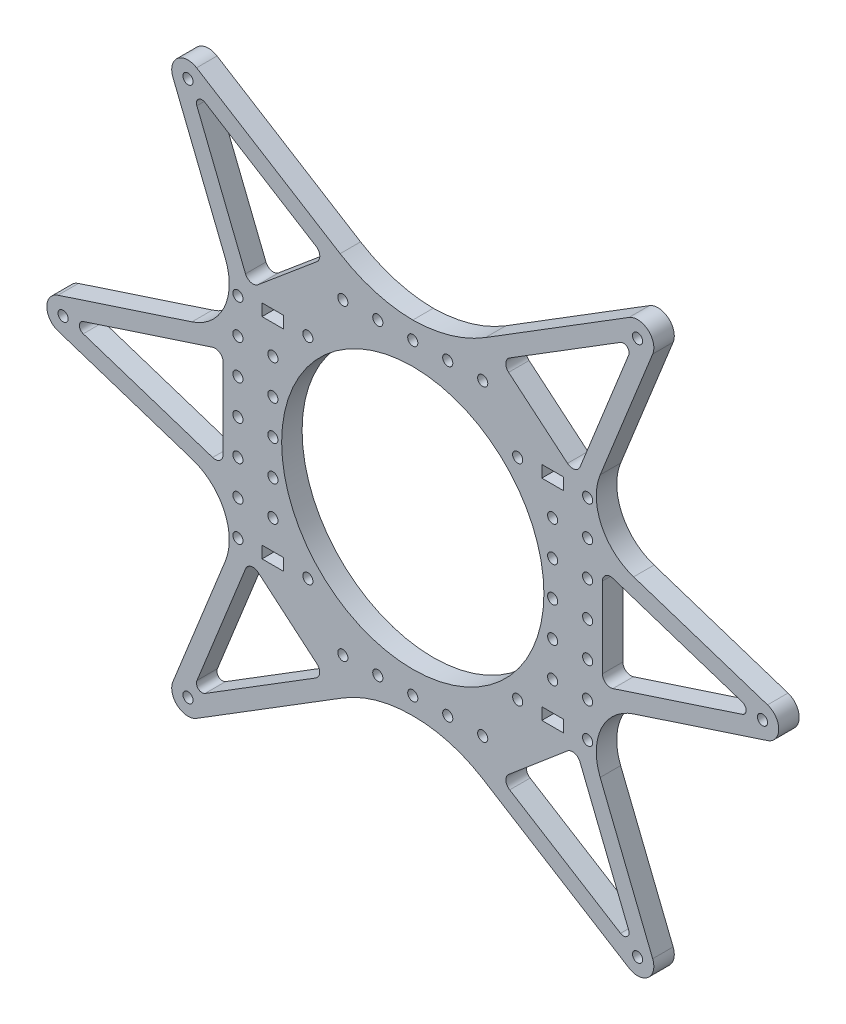
SolidWorks part; units mm, degrees
material "Acrylic (Medium-high impact)"
ref_plane "Front Plane" through (0, 0, 0) normal (0, 0, 1) x (1, 0, 0)
ref_plane "Top Plane" through (0, 0, 0) normal (0, 1, 0) x (1, 0, 0)
ref_plane "Right Plane" through (0, 0, 0) normal (1, 0, 0) x (0, 0, -1)
sketch "Sketch1" plane through (0, 0, 0) normal (0, 0, 1) x (1, 0, 0)
  line L0 (-447622.4345, 422.8828) -> (448935.6268, 422.8828) construction
  line L1 (587.9953, 497.7534) -> (603.0011, 460.347)
  line L2 (696.5962, 452.8828) -> (696.5962, 392.8828) construction
  line L3 (653.3971, 419.0702) -> (-31485.9834, -37883.1519) construction
  line L4 (699.6962, 394.5828) -> (693.4962, 391.1828) construction
  line L5 (699.6962, 391.1828) -> (693.4962, 394.5828) construction
  line L6 (594.8522, 494.09) -> (608.7611, 459.4182)
  line L7 (594.7755, 503.4426) -> (635.8224, 477.9343)
  line L8 (597.1925, 496.0537) -> (628.9222, 476.3355)
  line L9 (594.8522, 494.09) -> (597.1925, 496.0537) construction
  line L10 (699.6962, 391.1828) -> (693.4962, 391.1828)
  line L11 (693.4962, 394.5828) -> (693.4962, 391.1828)
  line L12 (699.6962, 394.5828) -> (693.4962, 394.5828)
  line L13 (594.7755, 503.4426) -> (587.9953, 497.7534) construction
  line L14 (629.1852, 472.64) -> (612.3548, 458.5175)
  line L15 (608.7611, 459.4182) -> (628.9222, 476.3355) construction
  line L16 (699.6962, 394.5828) -> (699.6962, 391.1828)
  line L17 (-343.4038, 422.8828) -> (49656.5962, 422.8828) construction
  line L18 (648.8948, 432.061) -> (-31490.4849, 38734.2822) construction
  line L19 (-347.3366, 471.8828) -> (49652.6634, 471.8828) construction
  line L20 (-347.2527, 373.8828) -> (49652.7473, 373.8828) construction
  line L21 (562.3601, 421.3552) -> (599.3601, 409.2322)
  line L22 (602.3601, 434.3594) -> (602.3601, 411.4062)
  line L23 (555.1462, 427.3082) -> (555.1462, 418.4573) construction
  line L24 (562.3601, 424.4103) -> (599.3601, 436.5334)
  line L25 (599.3601, 409.2322) -> (599.3601, 436.5334) construction
  line L26 (555.1462, 427.3082) -> (593.4467, 439.8574)
  line L27 (562.3601, 421.3552) -> (562.3601, 424.4103) construction
  line L28 (555.1462, 418.4573) -> (593.4517, 405.9065)
  line L29 (594.8972, 351.7804) -> (608.794, 386.3972)
  line L30 (594.7731, 342.323) -> (636.5319, 368.249)
  line L31 (612.3844, 387.288) -> (629.1561, 373.0862)
  line L32 (613.4962, 451.1828) -> (619.6962, 454.5828) construction
  line L33 (613.4962, 454.5828) -> (619.6962, 451.1828) construction
  line L34 (597.1926, 349.7104) -> (594.8972, 351.7804) construction
  line L35 (587.9969, 348.0128) -> (594.7731, 342.323) construction
  line L36 (628.8837, 369.3858) -> (608.794, 386.3972) construction
  line L37 (597.1926, 349.7104) -> (628.8837, 369.3858)
  line L38 (587.9969, 348.0128) -> (603.0082, 385.4059)
  line L39 (613.4962, 391.1828) -> (619.6962, 394.5828) construction
  line L40 (699.6962, 454.5828) -> (693.4962, 451.1828) construction
  line L41 (613.4962, 394.5828) -> (619.6962, 391.1828) construction
  line L42 (616.5962, 452.8828) -> (616.5962, 392.8828) construction
  line L43 (699.6962, 451.1828) -> (693.4962, 454.5828) construction
  line L44 (684.3087, 369.3858) -> (704.3983, 386.3972) construction
  line L45 (725.1955, 348.0128) -> (718.4193, 342.323) construction
  line L46 (715.9998, 349.7104) -> (718.2951, 351.7804) construction
  line L47 (750.8323, 421.3552) -> (750.8323, 424.4103) construction
  line L48 (713.8323, 409.2322) -> (713.8323, 436.5334) construction
  line L49 (758.0462, 427.3082) -> (758.0462, 418.4573) construction
  line L50 (704.4313, 459.4182) -> (684.2701, 476.3355) construction
  line L51 (718.4169, 503.4426) -> (725.1971, 497.7534) construction
  line L52 (718.3402, 494.09) -> (715.9998, 496.0537) construction
  line L53 (613.4962, 454.5828) -> (619.6962, 454.5828)
  line L54 (619.6962, 451.1828) -> (619.6962, 454.5828)
  line L55 (613.4962, 451.1828) -> (619.6962, 451.1828)
  line L56 (699.6962, 451.1828) -> (699.6962, 454.5828)
  line L57 (699.6962, 451.1828) -> (693.4962, 451.1828)
  line L58 (693.4962, 451.1828) -> (693.4962, 454.5828)
  line L59 (699.6962, 454.5828) -> (693.4962, 454.5828)
  line L60 (725.1955, 348.0128) -> (710.1842, 385.4059)
  line L61 (715.9998, 349.7104) -> (684.3087, 369.3858)
  line L62 (700.808, 387.288) -> (684.0362, 373.0862)
  line L63 (718.4193, 342.323) -> (676.6605, 368.249)
  line L64 (718.2951, 351.7804) -> (704.3983, 386.3972)
  line L65 (758.0462, 418.4573) -> (719.7407, 405.9065)
  line L66 (758.0462, 427.3082) -> (719.7457, 439.8574)
  line L67 (750.8323, 424.4103) -> (713.8323, 436.5334)
  line L68 (710.8323, 434.3594) -> (710.8323, 411.4062)
  line L69 (750.8323, 421.3552) -> (713.8323, 409.2322)
  line L70 (613.4962, 451.1828) -> (613.4962, 454.5828)
  line L71 (684.0071, 472.64) -> (700.8376, 458.5175)
  line L72 (613.4962, 394.5828) -> (613.4962, 391.1828)
  line L73 (613.4962, 394.5828) -> (619.6962, 394.5828)
  line L74 (619.6962, 394.5828) -> (619.6962, 391.1828)
  line L75 (715.9998, 496.0537) -> (684.2701, 476.3355)
  line L76 (718.4169, 503.4426) -> (677.3699, 477.9343)
  line L77 (718.3402, 494.09) -> (704.4313, 459.4182)
  line L78 (725.1971, 497.7534) -> (710.1912, 460.347)
  line L79 (613.4962, 391.1828) -> (619.6962, 391.1828)
  line L80 (706.5962, 432.8828) -> (696.5962, 432.8828) construction
  line L81 (706.5962, 422.8828) -> (706.5962, 432.8828) construction
  line L111 (656.5962, -513.6368) -> (656.5962, 49486.3632) construction
  arc A0 (597.1925, 496.0537) -> (594.8522, 494.09) centre (596.3441, 494.6884) ccw
  arc A1 (587.9953, 497.7534) -> (594.7755, 503.4426) centre (592.3174, 499.4872) cw
  circle A2 centre (592.3174, 499.4872) radius 1.45
  arc A4 (608.7611, 459.4182) -> (612.3548, 458.5175) centre (610.8843, 460.27) ccw
  arc A5 (629.1852, 472.64) -> (628.9222, 476.3355) centre (627.7147, 474.3924) ccw
  circle A6 centre (592.3174, 499.4872) radius 4.6569 construction
  circle A7 centre (706.5962, 432.8828) radius 1.45
  circle A8 centre (706.5962, 442.8828) radius 1.45
  circle A9 centre (706.5962, 452.8828) radius 1.45
  circle A10 centre (706.5962, 392.8828) radius 1.45
  arc A11 (555.1462, 418.4573) -> (555.1462, 427.3082) centre (556.5962, 422.8828) cw
  circle A12 centre (556.5962, 422.8828) radius 1.45
  circle A13 centre (646.5962, 378.8828) radius 1.45
  circle A14 centre (556.5962, 422.8828) radius 4.6569 construction
  arc A15 (562.3601, 424.4103) -> (562.3601, 421.3552) centre (562.8606, 422.8828) ccw
  circle A16 centre (656.5962, 422.8828) radius 37.5
  circle A18 centre (636.5962, 378.8828) radius 1.45
  arc A19 (602.3601, 434.3594) -> (599.3601, 436.5334) centre (600.0724, 434.3594) ccw
  circle A20 centre (706.5962, 402.8828) radius 1.45
  arc A21 (599.3601, 409.2322) -> (602.3601, 411.4062) centre (600.0724, 411.4062) ccw
  circle A22 centre (656.5962, 466.8828) radius 1.45
  circle A23 centre (696.5962, 432.8828) radius 1.45
  circle A24 centre (592.3174, 346.2783) radius 4.6557 construction
  arc A25 (628.8837, 369.3858) -> (629.1561, 373.0862) centre (627.6734, 371.3351) ccw
  arc A27 (594.7731, 342.323) -> (587.9969, 348.0128) centre (592.3174, 346.2783) cw
  arc A28 (594.8972, 351.7804) -> (597.1926, 349.7104) centre (596.3441, 351.0771) ccw
  arc A29 (612.3844, 387.288) -> (608.794, 386.3972) centre (610.9105, 385.5475) ccw
  circle A31 centre (592.3174, 346.2783) radius 1.45
  circle A32 centre (706.5962, 412.8828) radius 1.45
  arc A33 (593.4517, 405.9065) -> (603.0082, 385.4059) centre (588.6264, 391.1794) cw
  circle A34 centre (656.5962, 378.8828) radius 1.45
  arc A35 (593.4467, 439.8574) -> (603.0011, 460.347) centre (588.6231, 454.5791) ccw
  circle A37 centre (696.5962, 442.8828) radius 1.45
  circle A38 centre (696.5962, 402.8828) radius 1.45
  arc A39 (636.5319, 368.249) -> (656.5962, 373.8828) centre (656.2916, 336.4222) cw
  arc A40 (635.8224, 477.9343) -> (656.5962, 471.8828) centre (657.0335, 512.0663) ccw
  circle A41 centre (720.8749, 346.2783) radius 4.6557 construction
  circle A42 centre (756.5962, 422.8828) radius 4.6569 construction
  circle A43 centre (696.5962, 412.8828) radius 1.45
  circle A44 centre (646.5962, 466.8828) radius 1.45
  circle A45 centre (636.5962, 466.8828) radius 1.45
  circle A46 centre (720.8749, 499.4872) radius 4.6569 construction
  circle A47 centre (696.5962, 422.8828) radius 1.45
  circle A48 centre (676.5962, 466.8828) radius 1.45
  circle A49 centre (666.5962, 466.8828) radius 1.45
  circle A50 centre (706.5962, 422.8828) radius 1.45
  arc A51 (677.3699, 477.9343) -> (656.5962, 471.8828) centre (656.1588, 512.0663) cw
  arc A52 (676.6605, 368.249) -> (656.5962, 373.8828) centre (656.9008, 336.4222) ccw
  circle A53 centre (686.5962, 452.8828) radius 1.45
  circle A54 centre (686.5962, 392.8828) radius 1.45
  arc A55 (719.7457, 439.8574) -> (710.1912, 460.347) centre (724.5693, 454.5791) cw
  arc A56 (719.7407, 405.9065) -> (710.1842, 385.4059) centre (724.566, 391.1794) ccw
  circle A57 centre (626.5962, 392.8828) radius 1.45
  circle A58 centre (720.8749, 346.2783) radius 1.45
  arc A59 (700.808, 387.288) -> (704.3983, 386.3972) centre (702.2818, 385.5475) cw
  arc A60 (718.2951, 351.7804) -> (715.9998, 349.7104) centre (716.8483, 351.0771) cw
  arc A61 (718.4193, 342.323) -> (725.1955, 348.0128) centre (720.8749, 346.2783) ccw
  arc A62 (684.3087, 369.3858) -> (684.0362, 373.0862) centre (685.5189, 371.3351) cw
  arc A63 (713.8323, 409.2322) -> (710.8323, 411.4062) centre (713.12, 411.4062) cw
  arc A64 (710.8323, 434.3594) -> (713.8323, 436.5334) centre (713.12, 434.3594) cw
  circle A65 centre (676.5962, 378.8828) radius 1.45
  arc A66 (750.8323, 424.4103) -> (750.8323, 421.3552) centre (750.3318, 422.8828) cw
  circle A67 centre (666.5962, 378.8828) radius 1.45
  circle A68 centre (756.5962, 422.8828) radius 1.45
  arc A69 (758.0462, 418.4573) -> (758.0462, 427.3082) centre (756.5962, 422.8828) ccw
  circle A70 centre (626.5962, 452.8828) radius 1.45
  circle A71 centre (606.5962, 422.8828) radius 1.45
  circle A72 centre (616.5962, 422.8828) radius 1.45
  circle A73 centre (616.5962, 412.8828) radius 1.45
  arc A74 (684.0071, 472.64) -> (684.2701, 476.3355) centre (685.4776, 474.3924) cw
  arc A75 (704.4313, 459.4182) -> (700.8376, 458.5175) centre (702.3081, 460.27) cw
  circle A76 centre (720.8749, 499.4872) radius 1.45
  arc A77 (725.1971, 497.7534) -> (718.4169, 503.4426) centre (720.8749, 499.4872) ccw
  arc A78 (715.9998, 496.0537) -> (718.3402, 494.09) centre (716.8483, 494.6884) cw
  circle A79 centre (616.5962, 402.8828) radius 1.45
  circle A80 centre (616.5962, 442.8828) radius 1.45
  circle A81 centre (606.5962, 412.8828) radius 1.45
  circle A82 centre (616.5962, 432.8828) radius 1.45
  circle A83 centre (606.5962, 402.8828) radius 1.45
  circle A84 centre (606.5962, 392.8828) radius 1.45
  circle A85 centre (606.5962, 452.8828) radius 1.45
  circle A86 centre (606.5962, 442.8828) radius 1.45
  circle A87 centre (606.5962, 432.8828) radius 1.45
  circle A279 centre (626.5962, 466.8828) radius 1.45 [skipped]
  circle A282 centre (626.5962, 378.8828) radius 1.45 [skipped]
  point P2 (620.77, 465.5787)
  point P4 (604.6798, 472.924)
  point P5 (610.6788, 407.5004)
  point P6 (604.4937, 430.5743)
  point P7 (590.1096, 382.987)
  point P9 (656.5962, 422.8828)
  point P10 (592.2236, 451.9603)
  point P12 (560.2236, 451.9603)
  point P13 (615.5787, 412.0526)
  point P15 (596.4648, 452.5325)
  point P16 (593.7956, 519.1439)
  point P18 (562.0153, 451.7438)
  point P19 (589.0273, 503.4082)
  point P21 (557.1601, 445.912)
  point P22 (691.7574, 496.0365)
  point P23 (586.2073, 519.1355)
  point P25 (696.5962, 452.8828)
  point P27 (593.4054, 384.161)
  point P31 (706.9167, 384.1702)
  point P32 (709.3005, 386.1481)
  point P33 (712.3266, 520.5499)
  point P34 (710.2125, 451.5766)
  point P37 (593.7956, 519.1439)
  point P38 (704.5328, 382.1922)
  point P40 (675.1867, 401.4708)
  point P41 (685.2778, 409.8289)
  point P43 (705.5495, 376.706)
  point P44 (637.2651, 404.097)
  point P46 (743.1543, 445.9191)
  point P47 (656.5962, 422.8828)
  point P48 (685.1467, 493.2598)
  point P49 (742.2125, 451.5766)
  point P53 (695.1768, 484.8286)
  point P55 (708.8884, 517.1528)
  point P56 (706.5155, 519.1439)
  point P57 (714.1038, 519.1355)
  point P64 (708.6406, 384.393)
  point P66 (665.171, 499.4399)
  point P67 (704.1427, 521.135)
  point P80 (602.3601, 422.8828)
  point P86 (499.5503, 435.3778)
  point P106 (620.7703, 380.1871)
  point P114 (563.3616, 328.8714)
  point P127 (696.5962, 422.8828)
  point P143 (704.687, 438.4721)
  point P145 (738.2906, 448.6533)
  point P146 (704.7346, 451.575)
  point P147 (738.2991, 451.7509)
  point P148 (738.3077, 454.8484)
  point P241 (656.5962, 389.3729)
  point P244 (749.8308, 328.8714)
  point P245 (692.4221, 380.1871)
  point P246 (710.8323, 422.8828)
  point P247 (696.5962, 422.8828)
  point P248 (724.165, 503.4082)
  point P249 (692.4224, 465.5787)
  dimension "D2" = 2.9
  dimension "D3" = 6.2644
  dimension "D6" = 4
  dimension "D9" = 4
  dimension "D7" = 4
  dimension "D11" = 100
  dimension "D12" = 5
  dimension "D5" = 5
  dimension "D19" = 50
  dimension "D20" = 98
  dimension "D25" = 6.2644
  dimension "D13" = 3
  dimension "D15" = 38
  dimension "D18" = 40
  dimension "D39" = 3.4
  dimension "D37" = 2.9
  dimension "D38" = 75
  dimension "D8" = 50
  dimension "D10" = 30
  dimension "D14" = 50
  dimension "D16" = 37
  dimension "D17" = 2
  dimension "D21" = 5
  dimension "D22" = 5
  dimension "D24" = 5
  dimension "D26" = 3
  dimension "D27" = 10
  dimension "D29" = 5
  dimension "D30" = 6.2644
  dimension "D31" = 3
  dimension "D32" = 38
  dimension "D33" = 10
  dimension "D34" = 100
  dimension "D35" = 5
  dimension "D36" = 5
  dimension "D41" = 6.2
extrude "Boss-Extrude1" add sketch "Sketch1" along normal blind 5.85
